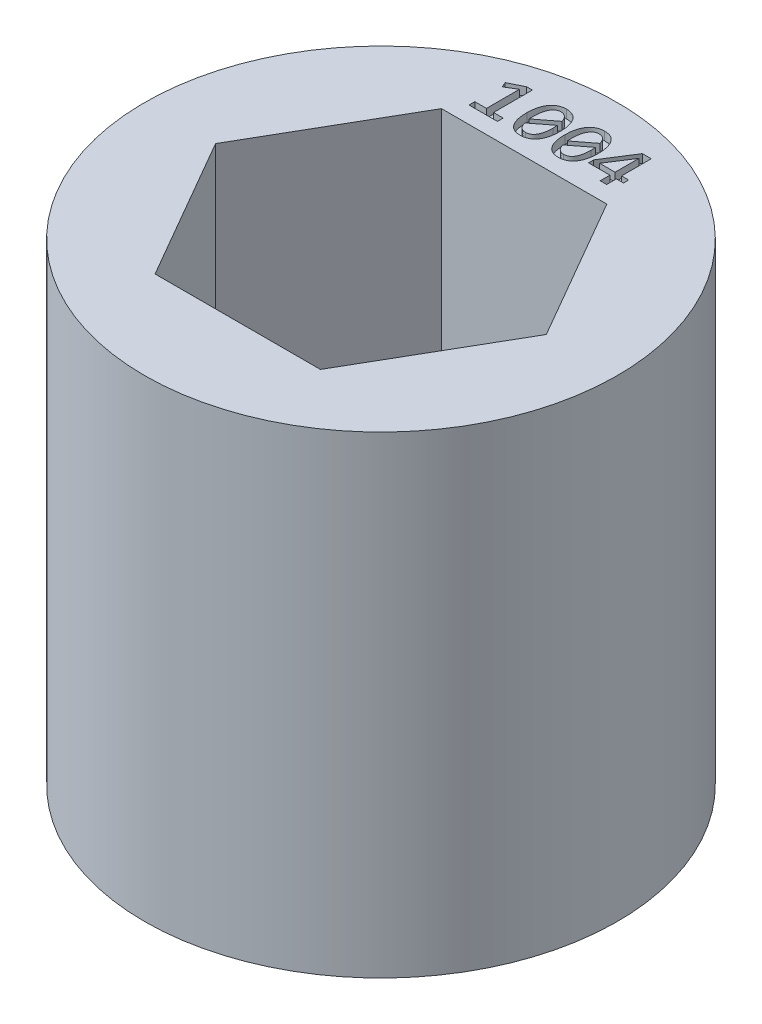
SolidWorks part; units mm, degrees
material "Nylon 101"
ref_plane "Front Plane" through (0, 0, 0) normal (0, 0, 1) x (1, 0, 0)
ref_plane "Top Plane" through (0, 0, 0) normal (0, 1, 0) x (1, 0, 0)
ref_plane "Right Plane" through (0, 0, 0) normal (1, 0, 0) x (0, 0, -1)
sketch "Sketch1" plane through (0, 0, 0) normal (0, 1, 0) x (1, 0, 0)
  line L1 (7.7723, 0) -> (3.8861, 6.731)
  line L2 (3.8861, 6.731) -> (-3.8861, 6.731)
  line L3 (-3.8861, 6.731) -> (-7.7723, 0)
  line L4 (-7.7723, 0) -> (-3.8861, -6.731)
  line L5 (-3.8861, -6.731) -> (3.8861, -6.731)
  line L6 (3.8861, -6.731) -> (7.7723, 0)
  circle A0 centre (0, 0) radius 6.731 construction
  circle A1 centre (0, 0) radius 11.1125
  dimension "D1" = 13.462
  dimension "D2" = 22.225
extrude "Boss-Extrude1" add sketch "Sketch1" along normal blind 22.225
sketch "Sketch2" plane through (0, 22.225, 0) normal (0, 1, 0) x (1, 0, 0)
  line L0 (-4.2615, 7.5247) -> (4.1119, 7.5247) construction
  line L1 (3.8861, 6.731) -> (-3.8861, 6.731) construction
  text T0 "1004" font "Consolas" height in points 8
  dimension "D1" = 0.7937
extrude "Cut-Extrude1" cut sketch "Sketch2" against normal blind 0.4
